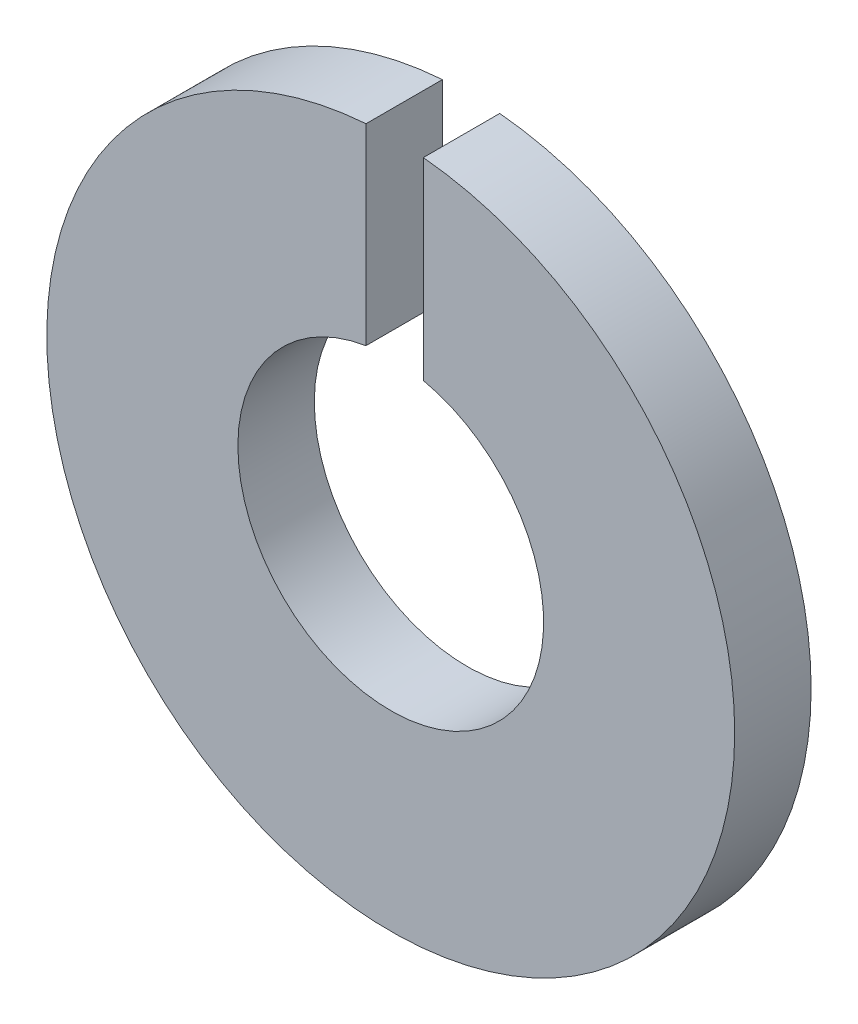
SolidWorks part; units mm, degrees
ref_plane "Front Plane" through (0, 0, 0) normal (0, 0, 1) x (1, 0, 0)
ref_plane "Top Plane" through (0, 0, 0) normal (0, 1, 0) x (1, 0, 0)
ref_plane "Right Plane" through (0, 0, 0) normal (1, 0, 0) x (0, 0, -1)
sketch "Sketch1" plane through (0, 0, 0) normal (0, 0, 1) x (1, 0, 0)
  line L2 (-0.6477, 8.9767) -> (-0.6477, 3.9472)
  line L4 (0.8523, 8.9596) -> (0.8523, 3.9082)
  arc A0 (-0.6477, 3.9472) -> (0.8523, 3.9082) centre (0, 0) ccw
  arc A1 (-0.6477, 8.9767) -> (0.8523, 8.9596) centre (0, 0) ccw
  circle A3 centre (0, 0) radius 9 construction
  circle A4 centre (0, 0) radius 4 construction
  point P4 (3.8252, 1.1695)
  point P9 (9, 0)
  dimension "D1" = 8
  dimension "D3" = 1.5
  dimension "D2" = 5
extrude "Boss-Extrude1" add sketch "Sketch1" along normal blind 2
